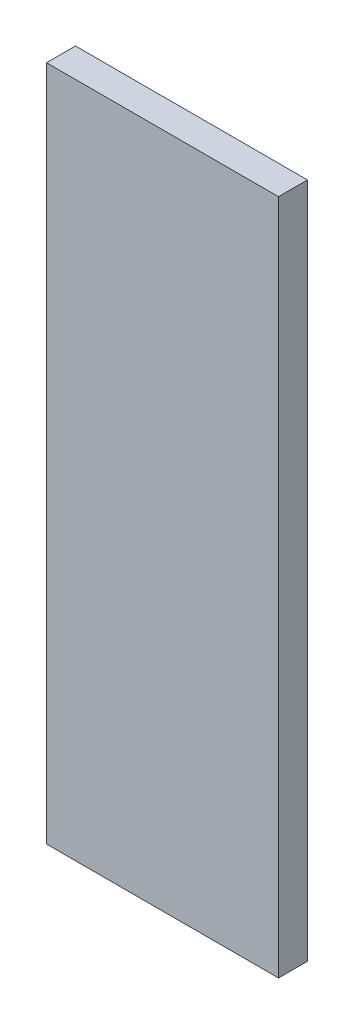
SolidWorks part; units mm, degrees
material "MDF"
ref_plane "Alzado" through (0, 0, 0) normal (0, 0, 1) x (1, 0, 0)
ref_plane "Planta" through (0, 0, 0) normal (0, 1, 0) x (1, 0, 0)
ref_plane "Vista lateral" through (0, 0, 0) normal (1, 0, 0) x (0, 0, -1)
sketch "Croquis1" plane through (0, 0, 0) normal (0, 0, 1) x (1, 0, 0)
  line L1 (-12, 35) -> (12, 35)
  line L2 (-12, 35) -> (-12, -35)
  line L3 (-12, -35) -> (12, -35)
  line L4 (12, 35) -> (12, -35)
  line L5 (-12, 35) -> (12, -35) construction
  line L6 (-12, -35) -> (12, 35) construction
  point P0 (0, 0)
  dimension "D1" = 70
  dimension "D2" = 24
extrude "Saliente-Extruir1" add sketch "Croquis1" along normal blind 3
